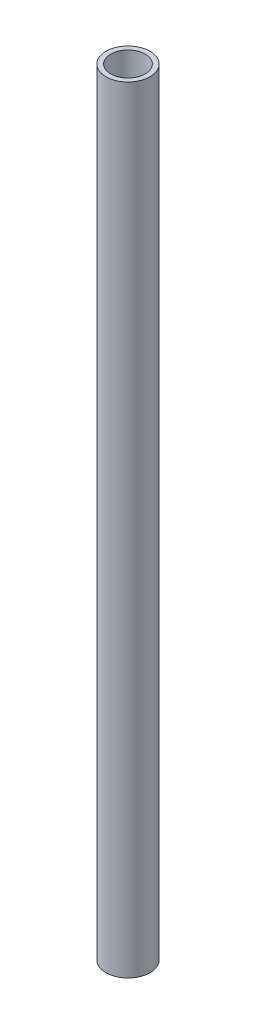
SolidWorks part; units mm, degrees
ref_plane "Front Plane" through (0, 0, 0) normal (0, 0, 1) x (1, 0, 0)
ref_plane "Top Plane" through (0, 0, 0) normal (0, 1, 0) x (1, 0, 0)
ref_plane "Right Plane" through (0, 0, 0) normal (1, 0, 0) x (0, 0, -1)
sketch "Sketch1" plane through (0, 0, 0) normal (0, 1, 0) x (1, 0, 0)
  circle A0 centre (0, 0) radius 7.9375
  circle A1 centre (0, 0) radius 6.2103
extrude "Boss-Extrude1" add sketch "Sketch1" along normal blind 279.4
